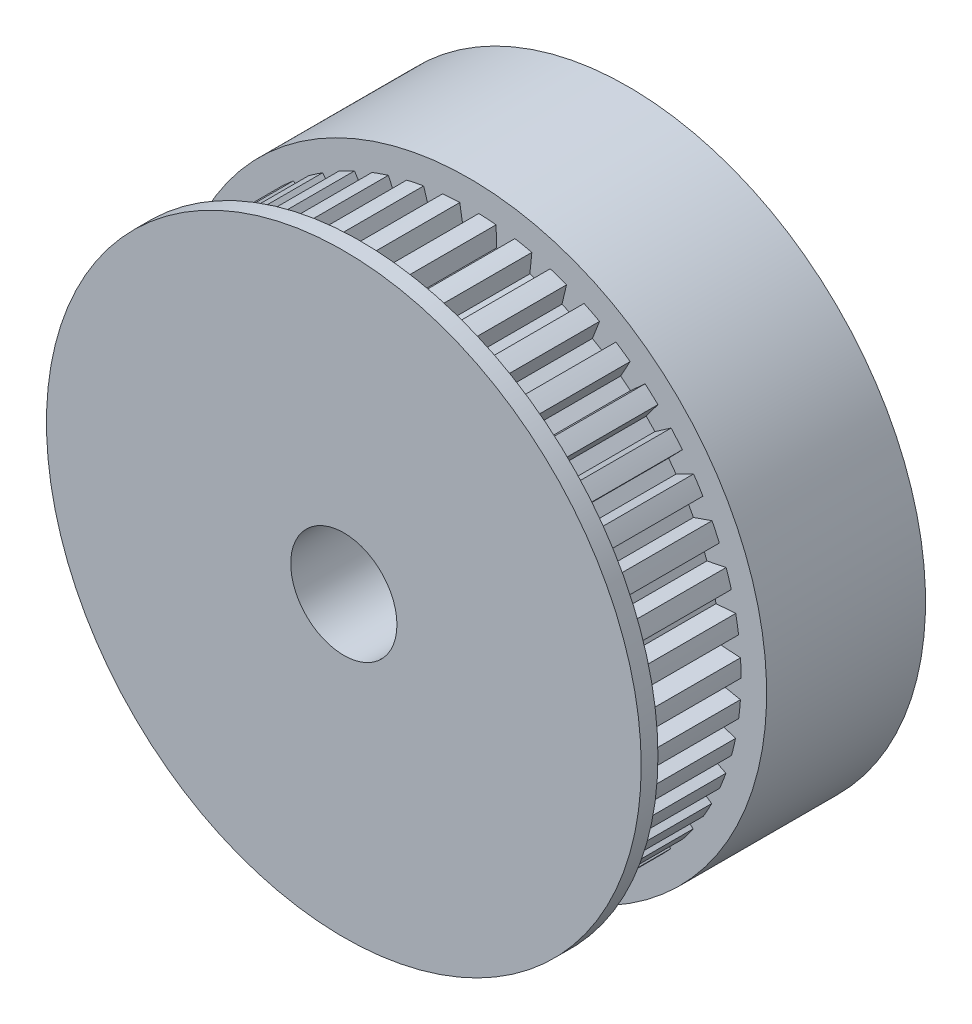
SolidWorks part; units mm, degrees
ref_plane "Front Plane" through (0, 0, 0) normal (0, 0, 1) x (1, 0, 0)
ref_plane "Top Plane" through (0, 0, 0) normal (0, 1, 0) x (1, 0, 0)
ref_plane "Right Plane" through (0, 0, 0) normal (1, 0, 0) x (0, 0, -1)
sketch "Sketch3" plane through (0, 0, 0) normal (0, 0, 1) x (1, 0, 0)
  circle A0 centre (0, 0) radius 16.25
  dimension "D1" = 32.5
extrude "Boss-Extrude2" add sketch "Sketch3" along normal mid plane 6.5
sketch "Sketch1" plane through (0, 0, 0) normal (0, 0, 1) x (1, 0, 0)
  line L0 (-0.375, 15.08) -> (0.375, 15.08)
  line L2 (-0.375, 15.08) -> (-0.6543, 16.7561)
  line L3 (-0.6543, 16.7561) -> (0.6543, 16.7561)
  line L4 (0.6543, 16.7561) -> (0.375, 15.08)
  line L5 (-0.5, 15.83) -> (0.5, 15.83) construction
  point P9 (0, 16.7561)
  point P10 (0, 15.08)
  dimension "D1" = 0.75
  dimension "D2" = 0.75
  dimension "D3" = 1
  dimension "D4" = 15.08
extrude "Cut-Extrude2" cut sketch "Sketch1" against normal through all both and the other way through all
pattern_circular "CirPattern3" count 47 over 360 about axis through (0, 0, 0) along (0, 0, 1) of "Cut-Extrude2"
sketch "Sketch5" plane through (0, 0, -3.25) normal (0, 0, -1) x (-1, 0, 0)
  circle A0 centre (0, 0) radius 17.78
  dimension "D1" = 35.56
extrude "Boss-Extrude3" add sketch "Sketch5" along normal blind 9.5
sketch "Sketch6" plane through (0, 0, 3.25) normal (0, 0, 1) x (1, 0, 0)
  circle A0 centre (0, 0) radius 17.78
  dimension "D1" = 35.56
extrude "Boss-Extrude4" add sketch "Sketch6" along normal blind 1 contours A0
sketch "Sketch7" plane through (0, 0, 4.25) normal (0, 0, 1) x (1, 0, 0)
  circle A0 centre (0, 0) radius 3.175
  dimension "D1" = 6.35
extrude "Cut-Extrude3" cut sketch "Sketch7" against normal through all
